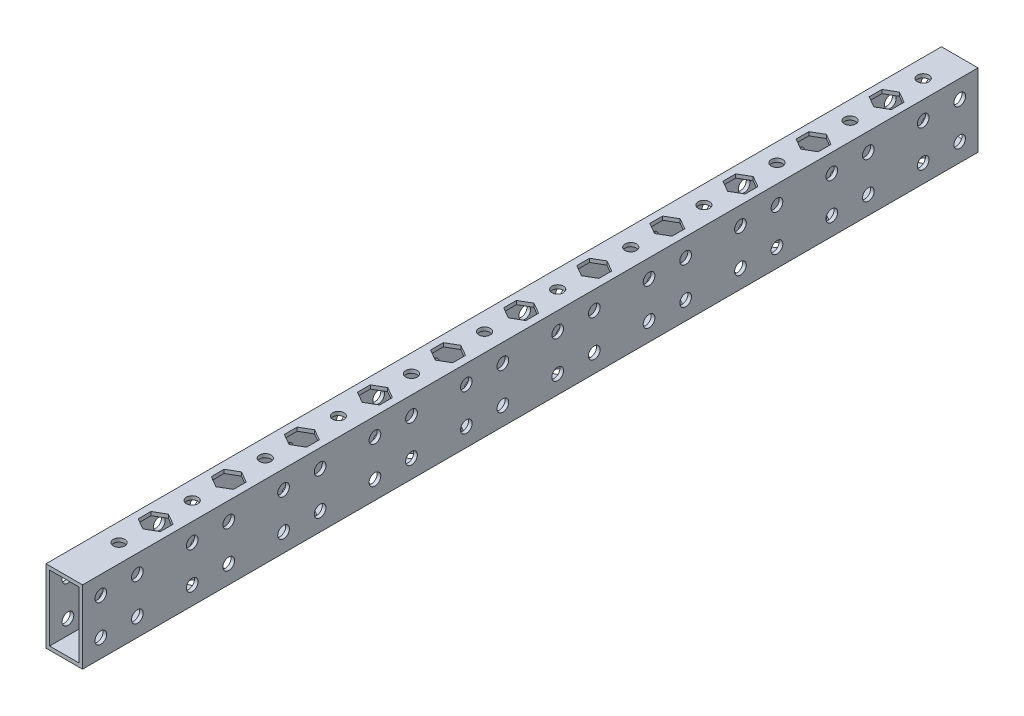
SolidWorks part; units mm, degrees
ref_plane "前视基准面" through (0, 0, 0) normal (0, 0, 1) x (1, 0, 0)
ref_plane "上视基准面" through (0, 0, 0) normal (0, 1, 0) x (1, 0, 0)
ref_plane "右视基准面" through (0, 0, 0) normal (1, 0, 0) x (0, 0, -1)
other "Configuration Table"
sketch "草图1" plane through (0, 0, 0) normal (0, 0, 1) x (1, 0, 0)
  line L1 (0, 0) -> (10, 0)
  line L2 (0, 0) -> (0, -20)
  line L3 (0, -20) -> (10, -20)
  line L4 (10, 0) -> (10, -20)
  dimension "D1" = 10
  dimension "D2" = 20
extrude "拉伸-薄壁1" add sketch "草图1" along normal blind 245 thin
sketch "草图2" plane through (0, -20, 0) normal (0, -1, 0) x (1, 0, 0)
  line L0 (0, 10) -> (10, 10) construction
  line L1 (10, 245) -> (10, 0) construction
  line L2 (0, 245) -> (0, 0) construction
  line L3 (5, 10) -> (5, 0) construction
  line L4 (0, 0) -> (10, 0) construction
  line L5 (5, 10) -> (5, 30) construction
  line L6 (5, 23.5) -> (1.9689, 21.75)
  line L7 (1.9689, 21.75) -> (1.9689, 18.25)
  line L8 (1.9689, 18.25) -> (5, 16.5)
  line L9 (5, 16.5) -> (8.0311, 18.25)
  line L10 (8.0311, 18.25) -> (8.0311, 21.75)
  line L11 (8.0311, 21.75) -> (5, 23.5)
  line L12 (5, 43.5) -> (1.9689, 41.75)
  line L13 (8.0311, 41.75) -> (5, 43.5)
  line L14 (8.0311, 38.25) -> (8.0311, 41.75)
  line L15 (1.9689, 38.25) -> (5, 36.5)
  line L16 (1.9689, 41.75) -> (1.9689, 38.25)
  line L17 (5, 36.5) -> (8.0311, 38.25)
  line L18 (5, 63.5) -> (1.9689, 61.75)
  line L19 (8.0311, 61.75) -> (5, 63.5)
  line L20 (8.0311, 58.25) -> (8.0311, 61.75)
  line L21 (1.9689, 58.25) -> (5, 56.5)
  line L22 (1.9689, 61.75) -> (1.9689, 58.25)
  line L23 (5, 56.5) -> (8.0311, 58.25)
  line L24 (5, 83.5) -> (1.9689, 81.75)
  line L25 (8.0311, 81.75) -> (5, 83.5)
  line L26 (8.0311, 78.25) -> (8.0311, 81.75)
  line L27 (1.9689, 78.25) -> (5, 76.5)
  line L28 (1.9689, 81.75) -> (1.9689, 78.25)
  line L29 (5, 76.5) -> (8.0311, 78.25)
  line L30 (5, 103.5) -> (1.9689, 101.75)
  line L31 (8.0311, 101.75) -> (5, 103.5)
  line L32 (8.0311, 98.25) -> (8.0311, 101.75)
  line L33 (1.9689, 98.25) -> (5, 96.5)
  line L34 (1.9689, 101.75) -> (1.9689, 98.25)
  line L35 (5, 96.5) -> (8.0311, 98.25)
  line L36 (5, 123.5) -> (1.9689, 121.75)
  line L37 (8.0311, 121.75) -> (5, 123.5)
  line L38 (8.0311, 118.25) -> (8.0311, 121.75)
  line L39 (1.9689, 118.25) -> (5, 116.5)
  line L40 (1.9689, 121.75) -> (1.9689, 118.25)
  line L41 (5, 116.5) -> (8.0311, 118.25)
  line L42 (5, 143.5) -> (1.9689, 141.75)
  line L43 (8.0311, 141.75) -> (5, 143.5)
  line L44 (8.0311, 138.25) -> (8.0311, 141.75)
  line L45 (1.9689, 138.25) -> (5, 136.5)
  line L46 (1.9689, 141.75) -> (1.9689, 138.25)
  line L47 (5, 136.5) -> (8.0311, 138.25)
  line L48 (5, 163.5) -> (1.9689, 161.75)
  line L49 (8.0311, 161.75) -> (5, 163.5)
  line L50 (8.0311, 158.25) -> (8.0311, 161.75)
  line L51 (1.9689, 158.25) -> (5, 156.5)
  line L52 (1.9689, 161.75) -> (1.9689, 158.25)
  line L53 (5, 156.5) -> (8.0311, 158.25)
  line L54 (5, 183.5) -> (1.9689, 181.75)
  line L55 (8.0311, 181.75) -> (5, 183.5)
  line L56 (8.0311, 178.25) -> (8.0311, 181.75)
  line L57 (1.9689, 178.25) -> (5, 176.5)
  line L58 (1.9689, 181.75) -> (1.9689, 178.25)
  line L59 (5, 176.5) -> (8.0311, 178.25)
  line L60 (5, 203.5) -> (1.9689, 201.75)
  line L61 (8.0311, 201.75) -> (5, 203.5)
  line L62 (8.0311, 198.25) -> (8.0311, 201.75)
  line L63 (1.9689, 198.25) -> (5, 196.5)
  line L64 (1.9689, 201.75) -> (1.9689, 198.25)
  line L65 (5, 196.5) -> (8.0311, 198.25)
  line L66 (5, 223.5) -> (1.9689, 221.75)
  line L67 (8.0311, 221.75) -> (5, 223.5)
  line L68 (8.0311, 218.25) -> (8.0311, 221.75)
  line L69 (1.9689, 218.25) -> (5, 216.5)
  line L70 (1.9689, 221.75) -> (1.9689, 218.25)
  line L71 (5, 216.5) -> (8.0311, 218.25)
  circle A4 centre (5, 10) radius 1.575
  circle A5 centre (5, 30) radius 1.575
  circle A6 centre (5, 50) radius 1.575
  circle A7 centre (5, 70) radius 1.575
  circle A8 centre (5, 90) radius 1.575
  circle A9 centre (5, 110) radius 1.575
  circle A10 centre (5, 130) radius 1.575
  circle A11 centre (5, 150) radius 1.575
  circle A12 centre (5, 170) radius 1.575
  circle A13 centre (5, 190) radius 1.575
  circle A14 centre (5, 210) radius 1.575
  circle A17 centre (5, 20) radius 3.0311 construction
  circle A18 centre (5, 40) radius 3.0311 construction
  circle A19 centre (5, 60) radius 3.0311 construction
  circle A20 centre (5, 80) radius 3.0311 construction
  circle A21 centre (5, 100) radius 3.0311 construction
  circle A22 centre (5, 120) radius 3.0311 construction
  circle A23 centre (5, 140) radius 3.0311 construction
  circle A24 centre (5, 160) radius 3.0311 construction
  circle A25 centre (5, 180) radius 3.0311 construction
  circle A26 centre (5, 200) radius 3.0311 construction
  circle A27 centre (5, 220) radius 3.0311 construction
  circle A29 centre (5, 230) radius 1.575
  dimension "D2" = 3.5
  dimension "D5" = 3.15
  dimension "D1" = 10
  dimension "D3" = 10
  dimension "D4" = 20
  dimension "D6" = 10
  dimension "D8" = 20
  dimension "D9" = 11
  dimension "D7" = 12
extrude "切除-拉伸1" cut sketch "草图2" against normal through all
sketch "草图3" plane through (0, 0, 0) normal (-1, 0, 0) x (0, 0, 1)
  line L0 (235, 0) -> (235, -20) construction
  line L1 (245, 0) -> (0, 0) construction
  line L2 (245, -20) -> (0, -20) construction
  line L3 (245, 0) -> (245, -20) construction
  line L4 (235, -10) -> (245, -10) construction
  line L5 (122.5, 0) -> (122.5, -20) construction
  line L6 (10, -10) -> (0, -10) construction
  line L7 (10, 0) -> (10, -20) construction
  circle A0 centre (240, -5) radius 1.6
  circle A1 centre (240, -15) radius 1.6
  circle A2 centre (230, -15) radius 1.6
  circle A3 centre (230, -5) radius 1.6
  circle A4 centre (15, -5) radius 1.6
  circle A5 centre (15, -15) radius 1.6
  circle A6 centre (5, -15) radius 1.6
  circle A7 centre (5, -5) radius 1.6
  circle A8 centre (30, -5) radius 1.6
  circle A9 centre (40, -5) radius 1.6
  circle A10 centre (40, -15) radius 1.6
  circle A11 centre (30, -15) radius 1.6
  circle A12 centre (55, -5) radius 1.6
  circle A13 centre (65, -5) radius 1.6
  circle A14 centre (65, -15) radius 1.6
  circle A15 centre (55, -15) radius 1.6
  circle A16 centre (80, -5) radius 1.6
  circle A17 centre (90, -5) radius 1.6
  circle A18 centre (90, -15) radius 1.6
  circle A19 centre (80, -15) radius 1.6
  circle A20 centre (105, -5) radius 1.6
  circle A21 centre (115, -5) radius 1.6
  circle A22 centre (115, -15) radius 1.6
  circle A23 centre (105, -15) radius 1.6
  circle A24 centre (140, -15) radius 1.6
  circle A25 centre (130, -15) radius 1.6
  circle A26 centre (130, -5) radius 1.6
  circle A27 centre (140, -5) radius 1.6
  circle A28 centre (165, -15) radius 1.6
  circle A29 centre (155, -15) radius 1.6
  circle A30 centre (155, -5) radius 1.6
  circle A31 centre (165, -5) radius 1.6
  circle A32 centre (190, -15) radius 1.6
  circle A33 centre (180, -15) radius 1.6
  circle A34 centre (180, -5) radius 1.6
  circle A35 centre (190, -5) radius 1.6
  circle A36 centre (215, -15) radius 1.6
  circle A37 centre (205, -15) radius 1.6
  circle A38 centre (205, -5) radius 1.6
  circle A39 centre (215, -5) radius 1.6
  dimension "D2" = 3.2
  dimension "D5" = 25
  dimension "D1" = 10
  dimension "D3" = 5
  dimension "D4" = 5
extrude "切除-拉伸2" cut sketch "草图3" against normal through all
